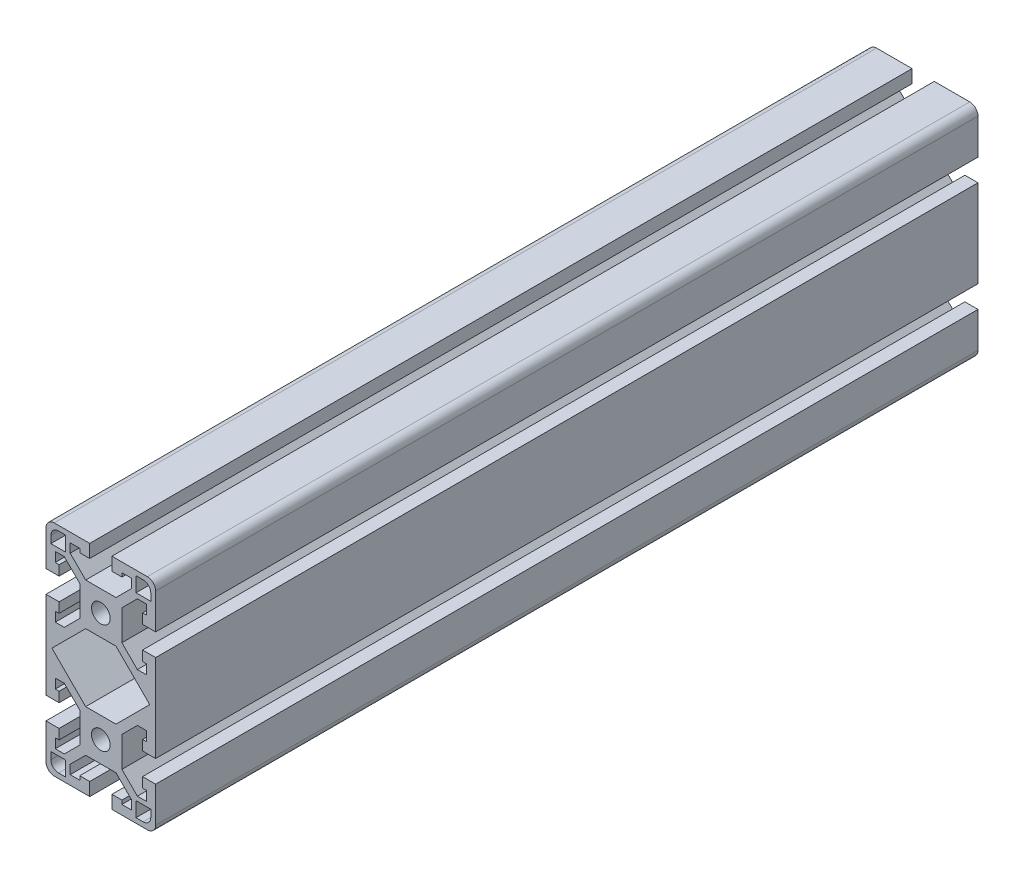
SolidWorks part; units mm, degrees
material "6063-T6"
ref_plane "Front Plane" through (0, 0, 0) normal (0, 0, 1) x (1, 0, 0)
ref_plane "Top Plane" through (0, 0, 0) normal (0, 1, 0) x (1, 0, 0)
ref_plane "Right Plane" through (0, 0, 0) normal (1, 0, 0) x (0, 0, -1)
sketch "Sketch1" plane through (0, 0, 0) normal (0, 1, 0) x (1, 0, 0)
  line L0 (0, -150) -> (0, 150)
  dimension "D1" = 300
other "40 series TS40-80LM-650037(1)"
ref_plane "Plane1" through (0, 0, 150) normal (0, 0, -1) x (-1, 0, 0)
sketch "Sketch2" plane through (0, 0, 150) normal (0, 0, -1) x (-1, 0, 0)
  line L2 (0, -27.681) -> (-5.5257, -27.681)
  line L3 (-5.5257, -27.681) -> (-11.176, -33.3313)
  line L4 (-7.6835, -36.6218) -> (-11.176, -36.6218)
  line L5 (-20, -37) -> (-20, -24.0488)
  line L6 (-4.0488, -40) -> (-17, -40)
  line L7 (-7.681, -20) -> (-7.681, -25.5257)
  line L8 (-7.681, -25.5257) -> (-13.3313, -31.176)
  line L9 (-16.6218, -31.176) -> (-16.6218, -27.6835)
  line L10 (-7.681, -14.4743) -> (-13.3313, -8.824)
  line L11 (-13.3313, -8.824) -> (-16.6218, -8.824)
  line L12 (-20, -24.0488) -> (-15.2248, -24.0488)
  line L13 (-20, 15.9512) -> (-20, -15.9512)
  line L14 (-5.5257, 12.319) -> (-17.8447, 0)
  line L15 (-5.5257, -12.319) -> (-17.8447, 0)
  line L16 (-7.681, -20) -> (-7.681, -14.4743)
  line L17 (-5.5257, -12.319) -> (0, -12.319)
  line L18 (7.681, -20) -> (7.681, -14.4743)
  line L19 (5.5257, -12.319) -> (17.8447, 0)
  line L20 (20, 15.9512) -> (15.2248, 15.9512)
  line L21 (4.0488, -35.2248) -> (7.6835, -35.2248)
  line L22 (7.681, 14.4743) -> (13.3313, 8.824)
  line L23 (7.6835, -36.6218) -> (7.6835, -35.2248)
  line L24 (4.0488, -35.2248) -> (4.0488, -40)
  line L25 (7.6835, -36.6218) -> (11.176, -36.6218)
  line L26 (11.176, -33.3313) -> (11.176, -36.6218)
  line L27 (7.681, -20) -> (7.681, -25.5257)
  line L28 (4.0488, -40) -> (17, -40)
  line L29 (20, -37) -> (20, -24.0488)
  line L30 (5.5257, -27.681) -> (11.176, -33.3313)
  line L31 (7.681, -25.5257) -> (13.3313, -31.176)
  line L32 (0, -12.319) -> (5.5257, -12.319)
  line L33 (0, -27.681) -> (5.5257, -27.681)
  line L35 (13.3313, 8.824) -> (16.6218, 8.824)
  line L36 (0, 12.319) -> (5.5257, 12.319)
  line L37 (-5.5257, 12.319) -> (0, 12.319)
  line L38 (16.6218, 8.824) -> (16.6218, 12.3165)
  line L39 (15.2248, 15.9512) -> (15.2248, 12.3165)
  line L40 (16.6218, 12.3165) -> (15.2248, 12.3165)
  line L41 (20, 24.0488) -> (15.2248, 24.0488)
  line L42 (0, 27.681) -> (5.5257, 27.681)
  line L43 (-4.0488, 40) -> (-17, 40)
  line L44 (-20, 37) -> (-20, 24.0488)
  line L45 (4.0488, 35.2248) -> (4.0488, 40)
  line L46 (16.6218, 31.176) -> (16.6218, 27.6835)
  line L47 (7.681, 20) -> (7.681, 25.5257)
  line L48 (13.3313, 31.176) -> (16.6218, 31.176)
  line L49 (15.2248, 24.0488) -> (15.2248, 27.6835)
  line L50 (7.681, 20) -> (7.681, 14.4743)
  line L51 (-7.681, 25.5257) -> (-7.681, 14.4743)
  line L52 (16.6218, 27.6835) -> (15.2248, 27.6835)
  line L53 (12.8372, 38.222) -> (12.8372, 32.8372)
  line L54 (20, 37) -> (20, 24.0488)
  line L55 (4.0488, 40) -> (17, 40)
  line L56 (12.8372, 38.222) -> (15.428, 38.222)
  line L57 (18.222, 35.428) -> (18.222, 32.8372)
  line L58 (12.8372, 32.8372) -> (18.222, 32.8372)
  line L59 (0, 27.681) -> (-5.5257, 27.681)
  line L60 (-4.0488, -35.2248) -> (-4.0488, -40)
  line L61 (-16.6218, -8.824) -> (-16.6218, -12.3165)
  line L62 (7.681, -14.4743) -> (13.3313, -8.824)
  line L63 (12.8372, -32.8372) -> (18.222, -32.8372)
  line L64 (20, 15.9512) -> (20, -15.9512)
  line L65 (7.681, 25.5257) -> (13.3313, 31.176)
  line L66 (5.5257, 27.681) -> (11.176, 33.3313)
  line L67 (5.5257, 12.319) -> (17.8447, 0)
  line L68 (-13.3313, -31.176) -> (-16.6218, -31.176)
  line L69 (-11.176, -33.3313) -> (-11.176, -36.6218)
  line L70 (-15.2248, -15.9512) -> (-15.2248, -12.3165)
  line L71 (-12.8372, -38.222) -> (-12.8372, -32.8372)
  line L72 (-12.8372, -38.222) -> (-15.428, -38.222)
  line L73 (-15.2248, -24.0488) -> (-15.2248, -27.6835)
  line L74 (-16.6218, -27.6835) -> (-15.2248, -27.6835)
  line L75 (-18.222, -35.428) -> (-18.222, -32.8372)
  line L76 (-12.8372, -32.8372) -> (-18.222, -32.8372)
  line L77 (-7.6835, -36.6218) -> (-7.6835, -35.2248)
  line L78 (-4.0488, -35.2248) -> (-7.6835, -35.2248)
  line L79 (-20, -15.9512) -> (-15.2248, -15.9512)
  line L80 (-16.6218, -12.3165) -> (-15.2248, -12.3165)
  line L81 (18.222, -35.428) -> (18.222, -32.8372)
  line L82 (12.8372, -38.222) -> (15.428, -38.222)
  line L83 (12.8372, -38.222) -> (12.8372, -32.8372)
  line L84 (16.6218, -12.3165) -> (15.2248, -12.3165)
  line L85 (20, -15.9512) -> (15.2248, -15.9512)
  line L86 (16.6218, -27.6835) -> (15.2248, -27.6835)
  line L87 (15.2248, -24.0488) -> (15.2248, -27.6835)
  line L88 (15.2248, -15.9512) -> (15.2248, -12.3165)
  line L89 (13.3313, -31.176) -> (16.6218, -31.176)
  line L90 (16.6218, -8.824) -> (16.6218, -12.3165)
  line L91 (20, -24.0488) -> (15.2248, -24.0488)
  line L92 (13.3313, -8.824) -> (16.6218, -8.824)
  line L93 (16.6218, -31.176) -> (16.6218, -27.6835)
  line L94 (11.176, 33.3313) -> (11.176, 36.6218)
  line L95 (7.6835, 36.6218) -> (11.176, 36.6218)
  line L96 (7.6835, 36.6218) -> (7.6835, 35.2248)
  line L97 (4.0488, 35.2248) -> (7.6835, 35.2248)
  line L98 (-4.0488, 35.2248) -> (-4.0488, 40)
  line L99 (-4.0488, 35.2248) -> (-7.6835, 35.2248)
  line L100 (-7.6835, 36.6218) -> (-7.6835, 35.2248)
  line L101 (-7.6835, 36.6218) -> (-11.176, 36.6218)
  line L102 (-11.176, 33.3313) -> (-11.176, 36.6218)
  line L103 (-5.5257, 27.681) -> (-11.176, 33.3313)
  line L104 (-18.222, 35.428) -> (-18.222, 32.8372)
  line L105 (-12.8372, 32.8372) -> (-18.222, 32.8372)
  line L106 (-7.681, 25.5257) -> (-13.3313, 31.176)
  line L107 (-13.3313, 31.176) -> (-16.6218, 31.176)
  line L108 (-16.6218, 31.176) -> (-16.6218, 27.6835)
  line L109 (-7.681, 14.4743) -> (-13.3313, 8.824)
  line L110 (-16.6218, 12.3165) -> (-15.2248, 12.3165)
  line L111 (-20, 15.9512) -> (-15.2248, 15.9512)
  line L112 (-15.2248, 15.9512) -> (-15.2248, 12.3165)
  line L113 (-16.6218, 8.824) -> (-16.6218, 12.3165)
  line L114 (-13.3313, 8.824) -> (-16.6218, 8.824)
  line L115 (-16.6218, 27.6835) -> (-15.2248, 27.6835)
  line L116 (-15.2248, 24.0488) -> (-15.2248, 27.6835)
  line L117 (-20, 24.0488) -> (-15.2248, 24.0488)
  line L118 (-12.8372, 38.222) -> (-15.428, 38.222)
  line L119 (-12.8372, 38.222) -> (-12.8372, 32.8372)
  arc A0 (-20, -37) -> (-17, -40) centre (-17, -37) ccw
  arc A1 (-20, 37) -> (-17, 40) centre (-17, 37) cw
  arc A2 (20, 37) -> (17, 40) centre (17, 37) ccw
  arc A3 (-15.428, -38.222) -> (-18.222, -35.428) centre (-15.428, -35.428) cw
  arc A4 (15.428, -38.222) -> (18.222, -35.428) centre (15.428, -35.428) ccw
  arc A5 (15.428, 38.222) -> (18.222, 35.428) centre (15.428, 35.428) cw
  arc A6 (-15.428, 38.222) -> (-18.222, 35.428) centre (-15.428, 35.428) ccw
  arc A7 (20, -37) -> (17, -40) centre (17, -37) cw
  circle A8 centre (0, -20) radius 3.35
  circle A9 centre (0, 20) radius 3.35
  point P1 (-20, 20)
  point P3 (-20, 40)
  point P34 (-20, 0)
  point P51 (20, 0)
  point P76 (0, 40)
  point P77 (20, 40)
  point P143 (20, 20)
  point P144 (20, -20)
  point P145 (-20, -20)
  point P146 (-20, -40)
  point P147 (0, -40)
  point P148 (20, -40)
  point P149 (0, 0)
  dimension "D1" = 6.7
hole_wizard "M8x1.25 Tapped Hole1" positions "Sketch3" profile "Sketch4" tap size "M8x1.25" standard "ANSI Metric"
sketch "Sketch3" plane through (0, 0, 150) normal (0, 0, 1) x (1, 0, 0)
  point P0 (0, -20)
  point P3 (0, 20)
sketch "Sketch4" plane through (0, -20, 150) normal (1, 0, 0) x (0, -1, 0)
  line L0 (0, 0) -> (0, 32.0429)
  line L1 (0, 32.0429) -> (3.4, 30)
  line L2 (3.4, 30) -> (3.4, 0)
  line L5 (3.4, 0) -> (0, 0)
  line L10 (0, 32.0429) -> (-3.4, 30) construction
  line L11 (0, -6.35) -> (0, 107.95) construction
  dimension "Tap Drill Dia." = 6.8
  dimension "Tap Drill Depth" = 30
  dimension "Drill Angle" = 118
cosmetic thread "Hole Thread1" parameters "D1"=25, "D2"=8
cosmetic thread "Hole Thread2" parameters "D1"=25, "D2"=8
mirror "Mirror1" about plane through (0, 0, 0) normal (0, 0, 1) of "M8x1.25 Tapped Hole1"
cosmetic thread "Hole Thread3" parameters "D1"=25, "D2"=8
cosmetic thread "Hole Thread4" parameters "D1"=25, "D2"=8
